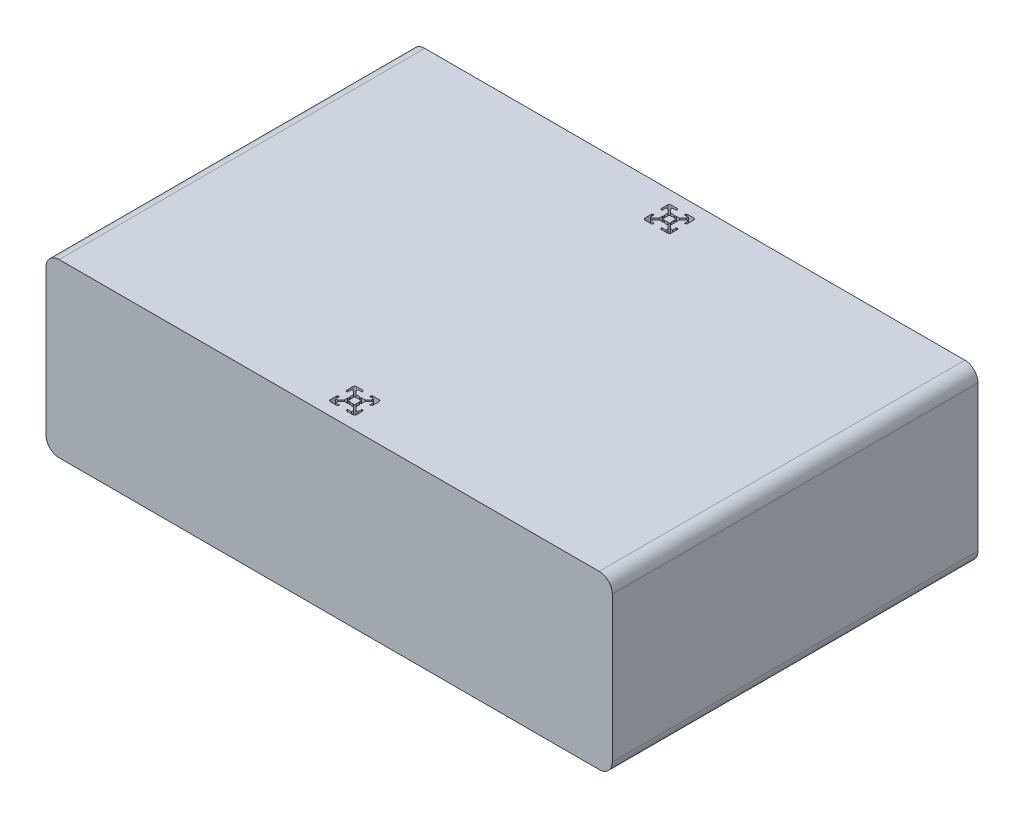
SolidWorks part; units mm, degrees
material "PE haute densité"
ref_plane "Plan de face" through (0, 0, 0) normal (0, 0, 1) x (1, 0, 0)
ref_plane "Plan de dessus" through (0, 0, 0) normal (0, 1, 0) x (1, 0, 0)
ref_plane "Plan de droite" through (0, 0, 0) normal (1, 0, 0) x (0, 0, -1)
sketch "Esquisse1" plane through (0, 0, 0) normal (0, 1, 0) x (1, 0, 0)
  line L1 (-216, 139.5) -> (216, 139.5)
  line L2 (-216, 139.5) -> (-216, -139.5)
  line L3 (-216, -139.5) -> (216, -139.5)
  line L4 (216, 139.5) -> (216, -139.5)
  line L5 (-216, 139.5) -> (216, -139.5) construction
  line L6 (-216, -139.5) -> (216, 139.5) construction
  point P0 (0, 0)
  dimension "D1" = 432
  dimension "D2" = 279
extrude "Boss.-Extru.1" add sketch "Esquisse1" along normal blind 131
fillet "Congé1" radius 10 4 edges at (-216, 0, 0) (-216, 131, 0) (216, 0, 0) (216, 131, 0)
sketch "Esquisse2" plane through (0, 131, 0) normal (0, 1, 0) x (1, 0, 0)
  circle A0 centre (0, 0) radius 25
  dimension "D1" = 50
sketch "Esquisse3" plane through (0, 131, 0) normal (0, 1, 0) x (1, 0, 0)
  line L0 (0, 0) -> (0, -120) construction
  line L79 (0, 0) -> (0, 120) construction
  point P3 (0, 0)
  point P167 (0, 0)
  point P168 (0, 0)
  point P169 (0, 0)
  line B0 (-3.0009, 121.9496) -> (-2.4359, 121.2763)
  line B1 (-2.4375, 118.7268) -> (-3.0032, 118.0527)
  line B2 (-3.0032, 118.0527) -> (-1.9496, 116.9991)
  line B3 (-1.9496, 116.9991) -> (-1.2763, 117.5641)
  line B4 (1.2732, 117.5625) -> (1.9473, 116.9968)
  line B5 (1.9473, 116.9968) -> (3.0009, 118.0504)
  line B6 (3.0009, 118.0504) -> (2.4359, 118.7237)
  line B7 (2.4375, 121.2732) -> (3.0032, 121.9473)
  line B8 (3.0032, 121.9473) -> (1.9496, 123.0009)
  line B9 (1.9496, 123.0009) -> (1.2763, 122.4359)
  line B10 (-1.2732, 122.4375) -> (-1.9473, 123.0032)
  line B11 (-1.9473, 123.0032) -> (-3.0009, 121.9496)
  line B12 (-10, 116.5) -> (-10, 111.5)
  line B13 (-8.5, 110) -> (-3.5, 110)
  line B14 (-3.5, 110) -> (-3.5, 110.5)
  line B15 (-3.5, 110.5) -> (-3, 110.5)
  line B16 (-3, 110.5) -> (-3, 111.5)
  line B17 (-3, 111.5) -> (-6, 111.5)
  line B18 (-6, 111.5) -> (-6, 112.9393)
  line B19 (-6, 112.9393) -> (-3.4393, 115.5)
  line B20 (-3.4393, 115.5) -> (-0.866, 115.5)
  line B21 (-0.866, 115.5) -> (0, 116)
  line B22 (0, 116) -> (0.866, 115.5)
  line B23 (0.866, 115.5) -> (3.4393, 115.5)
  line B24 (3.4393, 115.5) -> (6, 112.9393)
  line B25 (6, 112.9393) -> (6, 111.5)
  line B26 (6, 111.5) -> (3, 111.5)
  line B27 (3, 111.5) -> (3, 110.5)
  line B28 (3, 110.5) -> (3.5, 110.5)
  line B29 (3.5, 110.5) -> (3.5, 110)
  line B30 (3.5, 110) -> (8.5, 110)
  line B31 (10, 111.5) -> (10, 116.5)
  line B32 (10, 116.5) -> (9.5, 116.5)
  line B33 (9.5, 116.5) -> (9.5, 117)
  line B34 (9.5, 117) -> (8.5, 117)
  line B35 (8.5, 117) -> (8.5, 114)
  line B36 (8.5, 114) -> (7.0607, 114)
  line B37 (7.0607, 114) -> (4.5, 116.5607)
  line B38 (4.5, 116.5607) -> (4.5, 119.134)
  line B39 (4.5, 119.134) -> (4, 120)
  line B40 (4, 120) -> (4.5, 120.866)
  line B41 (4.5, 120.866) -> (4.5, 123.4393)
  line B42 (4.5, 123.4393) -> (7.0607, 126)
  line B43 (7.0607, 126) -> (8.5, 126)
  line B44 (8.5, 126) -> (8.5, 123)
  line B45 (8.5, 123) -> (9.5, 123)
  line B46 (9.5, 123) -> (9.5, 123.5)
  line B47 (9.5, 123.5) -> (10, 123.5)
  line B48 (10, 123.5) -> (10, 128.5)
  line B49 (8.5, 130) -> (3.5, 130)
  line B50 (3.5, 130) -> (3.5, 129.5)
  line B51 (3.5, 129.5) -> (3, 129.5)
  line B52 (3, 129.5) -> (3, 128.5)
  line B53 (3, 128.5) -> (6, 128.5)
  line B54 (6, 128.5) -> (6, 127.0607)
  line B55 (6, 127.0607) -> (3.4393, 124.5)
  line B56 (3.4393, 124.5) -> (0.866, 124.5)
  line B57 (0.866, 124.5) -> (0, 124)
  line B58 (0, 124) -> (-0.866, 124.5)
  line B59 (-0.866, 124.5) -> (-3.4393, 124.5)
  line B60 (-3.4393, 124.5) -> (-6, 127.0607)
  line B61 (-6, 127.0607) -> (-6, 128.5)
  line B62 (-6, 128.5) -> (-3, 128.5)
  line B63 (-3, 128.5) -> (-3, 129.5)
  line B64 (-3, 129.5) -> (-3.5, 129.5)
  line B65 (-3.5, 129.5) -> (-3.5, 130)
  line B66 (-3.5, 130) -> (-8.5, 130)
  line B67 (-10, 128.5) -> (-10, 123.5)
  line B68 (-10, 123.5) -> (-9.5, 123.5)
  line B69 (-9.5, 123.5) -> (-9.5, 123)
  line B70 (-9.5, 123) -> (-8.5, 123)
  line B71 (-8.5, 123) -> (-8.5, 126)
  line B72 (-8.5, 126) -> (-7.0607, 126)
  line B73 (-7.0607, 126) -> (-4.5, 123.4393)
  line B74 (-4.5, 123.4393) -> (-4.5, 120.866)
  line B75 (-4.5, 120.866) -> (-4, 120)
  line B76 (-4, 120) -> (-4.5, 119.134)
  line B77 (-4.5, 119.134) -> (-4.5, 116.5607)
  line B78 (-4.5, 116.5607) -> (-7.0607, 114)
  line B79 (-7.0607, 114) -> (-8.5, 114)
  line B80 (-8.5, 114) -> (-8.5, 117)
  line B81 (-8.5, 117) -> (-9.5, 117)
  line B82 (-9.5, 117) -> (-9.5, 116.5)
  line B83 (-9.5, 116.5) -> (-10, 116.5)
  arc B84 (-10, 111.5) -> (-8.5, 110) centre (-8.5, 111.5) ccw
  arc B85 (8.5, 110) -> (10, 111.5) centre (8.5, 111.5) ccw
  arc B86 (10, 128.5) -> (8.5, 130) centre (8.5, 128.5) ccw
  arc B87 (-8.5, 130) -> (-10, 128.5) centre (-8.5, 128.5) ccw
  arc B88 (-2.4359, 121.2763) -> (-2.4375, 118.7268) centre (0, 120) ccw
  arc B89 (-1.2763, 117.5641) -> (1.2732, 117.5625) centre (0, 120) ccw
  arc B90 (2.4359, 118.7237) -> (2.4375, 121.2732) centre (0, 120) ccw
  arc B91 (1.2763, 122.4359) -> (-1.2732, 122.4375) centre (0, 120) ccw
  line B92 (-3.0009, -118.0504) -> (-2.4359, -118.7237)
  line B93 (-2.4375, -121.2732) -> (-3.0032, -121.9473)
  line B94 (-3.0032, -121.9473) -> (-1.9496, -123.0009)
  line B95 (-1.9496, -123.0009) -> (-1.2763, -122.4359)
  line B96 (1.2732, -122.4375) -> (1.9473, -123.0032)
  line B97 (1.9473, -123.0032) -> (3.0009, -121.9496)
  line B98 (3.0009, -121.9496) -> (2.4359, -121.2763)
  line B99 (2.4375, -118.7268) -> (3.0032, -118.0527)
  line B100 (3.0032, -118.0527) -> (1.9496, -116.9991)
  line B101 (1.9496, -116.9991) -> (1.2763, -117.5641)
  line B102 (-1.2732, -117.5625) -> (-1.9473, -116.9968)
  line B103 (-1.9473, -116.9968) -> (-3.0009, -118.0504)
  line B104 (-10, -123.5) -> (-10, -128.5)
  line B105 (-8.5, -130) -> (-3.5, -130)
  line B106 (-3.5, -130) -> (-3.5, -129.5)
  line B107 (-3.5, -129.5) -> (-3, -129.5)
  line B108 (-3, -129.5) -> (-3, -128.5)
  line B109 (-3, -128.5) -> (-6, -128.5)
  line B110 (-6, -128.5) -> (-6, -127.0607)
  line B111 (-6, -127.0607) -> (-3.4393, -124.5)
  line B112 (-3.4393, -124.5) -> (-0.866, -124.5)
  line B113 (-0.866, -124.5) -> (0, -124)
  line B114 (0, -124) -> (0.866, -124.5)
  line B115 (0.866, -124.5) -> (3.4393, -124.5)
  line B116 (3.4393, -124.5) -> (6, -127.0607)
  line B117 (6, -127.0607) -> (6, -128.5)
  line B118 (6, -128.5) -> (3, -128.5)
  line B119 (3, -128.5) -> (3, -129.5)
  line B120 (3, -129.5) -> (3.5, -129.5)
  line B121 (3.5, -129.5) -> (3.5, -130)
  line B122 (3.5, -130) -> (8.5, -130)
  line B123 (10, -128.5) -> (10, -123.5)
  line B124 (10, -123.5) -> (9.5, -123.5)
  line B125 (9.5, -123.5) -> (9.5, -123)
  line B126 (9.5, -123) -> (8.5, -123)
  line B127 (8.5, -123) -> (8.5, -126)
  line B128 (8.5, -126) -> (7.0607, -126)
  line B129 (7.0607, -126) -> (4.5, -123.4393)
  line B130 (4.5, -123.4393) -> (4.5, -120.866)
  line B131 (4.5, -120.866) -> (4, -120)
  line B132 (4, -120) -> (4.5, -119.134)
  line B133 (4.5, -119.134) -> (4.5, -116.5607)
  line B134 (4.5, -116.5607) -> (7.0607, -114)
  line B135 (7.0607, -114) -> (8.5, -114)
  line B136 (8.5, -114) -> (8.5, -117)
  line B137 (8.5, -117) -> (9.5, -117)
  line B138 (9.5, -117) -> (9.5, -116.5)
  line B139 (9.5, -116.5) -> (10, -116.5)
  line B140 (10, -116.5) -> (10, -111.5)
  line B141 (8.5, -110) -> (3.5, -110)
  line B142 (3.5, -110) -> (3.5, -110.5)
  line B143 (3.5, -110.5) -> (3, -110.5)
  line B144 (3, -110.5) -> (3, -111.5)
  line B145 (3, -111.5) -> (6, -111.5)
  line B146 (6, -111.5) -> (6, -112.9393)
  line B147 (6, -112.9393) -> (3.4393, -115.5)
  line B148 (3.4393, -115.5) -> (0.866, -115.5)
  line B149 (0.866, -115.5) -> (0, -116)
  line B150 (0, -116) -> (-0.866, -115.5)
  line B151 (-0.866, -115.5) -> (-3.4393, -115.5)
  line B152 (-3.4393, -115.5) -> (-6, -112.9393)
  line B153 (-6, -112.9393) -> (-6, -111.5)
  line B154 (-6, -111.5) -> (-3, -111.5)
  line B155 (-3, -111.5) -> (-3, -110.5)
  line B156 (-3, -110.5) -> (-3.5, -110.5)
  line B157 (-3.5, -110.5) -> (-3.5, -110)
  line B158 (-3.5, -110) -> (-8.5, -110)
  line B159 (-10, -111.5) -> (-10, -116.5)
  line B160 (-10, -116.5) -> (-9.5, -116.5)
  line B161 (-9.5, -116.5) -> (-9.5, -117)
  line B162 (-9.5, -117) -> (-8.5, -117)
  line B163 (-8.5, -117) -> (-8.5, -114)
  line B164 (-8.5, -114) -> (-7.0607, -114)
  line B165 (-7.0607, -114) -> (-4.5, -116.5607)
  line B166 (-4.5, -116.5607) -> (-4.5, -119.134)
  line B167 (-4.5, -119.134) -> (-4, -120)
  line B168 (-4, -120) -> (-4.5, -120.866)
  line B169 (-4.5, -120.866) -> (-4.5, -123.4393)
  line B170 (-4.5, -123.4393) -> (-7.0607, -126)
  line B171 (-7.0607, -126) -> (-8.5, -126)
  line B172 (-8.5, -126) -> (-8.5, -123)
  line B173 (-8.5, -123) -> (-9.5, -123)
  line B174 (-9.5, -123) -> (-9.5, -123.5)
  line B175 (-9.5, -123.5) -> (-10, -123.5)
  arc B176 (-10, -128.5) -> (-8.5, -130) centre (-8.5, -128.5) ccw
  arc B177 (8.5, -130) -> (10, -128.5) centre (8.5, -128.5) ccw
  arc B178 (10, -111.5) -> (8.5, -110) centre (8.5, -111.5) ccw
  arc B179 (-8.5, -110) -> (-10, -111.5) centre (-8.5, -111.5) ccw
  arc B180 (-2.4359, -118.7237) -> (-2.4375, -121.2732) centre (0, -120) ccw
  arc B181 (-1.2763, -122.4359) -> (1.2732, -122.4375) centre (0, -120) ccw
  arc B182 (2.4359, -121.2763) -> (2.4375, -118.7268) centre (0, -120) ccw
  arc B183 (1.2763, -117.5641) -> (-1.2732, -117.5625) centre (0, -120) ccw
  dimension "D1" = 120
  dimension "125" = 120
sketch_block_instance "Bloc1-1"
sketch_block "Bloc1"
sketch_block_instance "Bloc1-3"
extrude "Enlèv. mat.-Extru.2" cut sketch "Esquisse3" against normal blind 100
